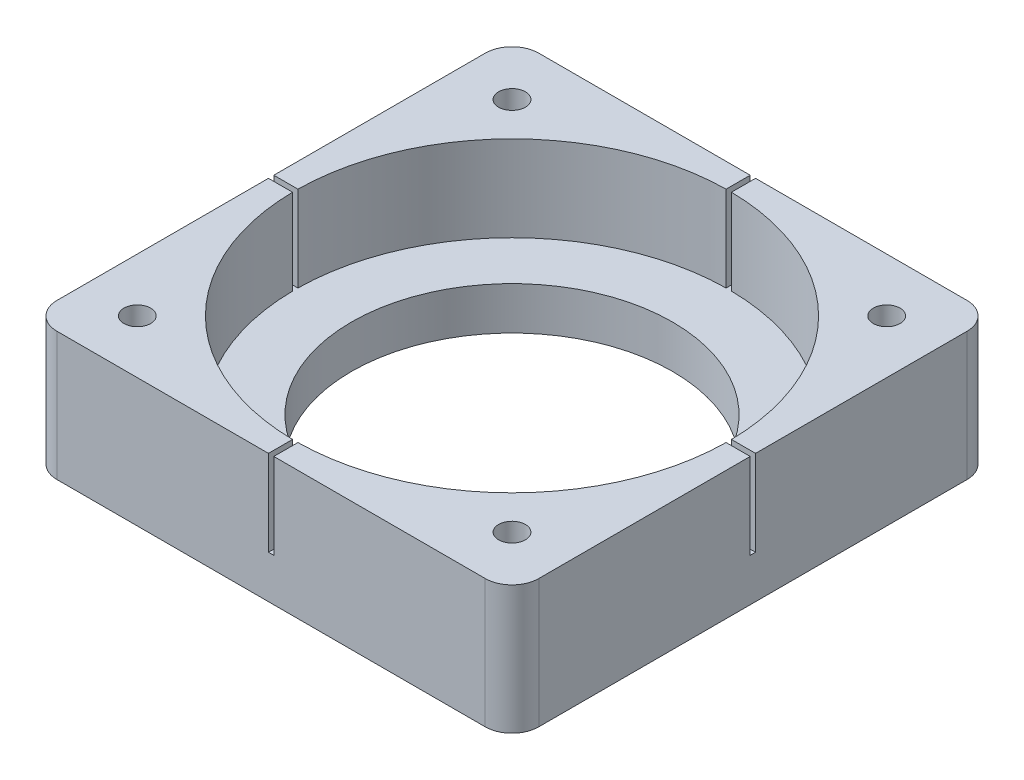
SolidWorks part; units mm, degrees
ref_plane "Front Plane" through (0, 0, 0) normal (0, 0, 1) x (1, 0, 0)
ref_plane "Top Plane" through (0, 0, 0) normal (0, 1, 0) x (1, 0, 0)
ref_plane "Right Plane" through (0, 0, 0) normal (1, 0, 0) x (0, 0, -1)
sketch "Sketch1" plane through (0, 0, 0) normal (0, 1, 0) x (1, 0, 0)
  line L5 (-45, -45) -> (45, -45)
  line L6 (-45, -45) -> (-45, 45)
  line L11 (-45, 45) -> (45, 45)
  line L12 (45, -45) -> (45, 45)
  line L13 (-45, -45) -> (45, 45) construction
  line L14 (-45, 45) -> (45, -45) construction
  line L15 (-35, -35) -> (35, -35) construction
  line L16 (-35, -35) -> (-35, 35) construction
  line L17 (-35, 35) -> (35, 35) construction
  line L18 (35, -35) -> (35, 35) construction
  line L19 (-35, -35) -> (35, 35) construction
  line L20 (-35, 35) -> (35, -35) construction
  circle A0 centre (0, 0) radius 34
  point P0 (0, 0)
  point P6 (0, 0)
  dimension "D3" = 68
  dimension "D1" = 70
  dimension "D2" = 90
extrude "Boss-Extrude1" add sketch "Sketch1" along normal blind 24 contours A0 | L5 L12 L11 L6 A0
sketch "Sketch2" plane through (0, 24, 0) normal (0, 1, 0) x (1, 0, 0)
  circle A0 centre (0, 0) radius 40.5
  dimension "D1" = 81
extrude "Cut-Extrude1" cut sketch "Sketch2" against normal blind 16
sketch "Sketch3" plane through (0, 8, 0) normal (0, 1, 0) x (1, 0, 0)
  circle A0 centre (0, 0) radius 12.7
  dimension "D1" = 25.4
extrude "Cut-Extrude2" cut sketch "Sketch3" against normal blind 19
hole_wizard "M6x1.0 Tapped Hole1" positions "Sketch4" profile "Sketch6" tap size "M6x1.0" standard "ANSI Metric" end condition through all
sketch "Sketch4" plane through (0, 0, 0) normal (0, -1, 0) x (-1, 0, 0)
  point P0 (35, 35)
  point P3 (35, -35)
  point P6 (-35, -35)
  point P9 (-35, 35)
cosmetic thread "Hole Thread1" parameters "D2"=6
cosmetic thread "Hole Thread2" parameters "D2"=6
cosmetic thread "Hole Thread3" parameters "D2"=6
cosmetic thread "Hole Thread4" parameters "D2"=6
sketch "Sketch6" plane through (-35, 0, -35) normal (1, 0, 0) x (0, 0, -1)
  line L0 (0, 0) -> (0, 24)
  line L1 (0, 24) -> (2.5, 24)
  line L2 (2.5, 24) -> (2.5, 0)
  line L5 (2.5, 0) -> (0, 0)
  line L11 (0, -6.35) -> (0, 107.95) construction
  dimension "Thru Tap Drill Dia." = 5
  dimension "Thru Tap Drill Depth" = 24
fillet "Fillet1" radius 5 4 edges at (45, 12, -45) (-45, 12, -45) (45, 12, 45) (-45, 12, 45)
chamfer "Chamfer1" [suppressed] distance 1 angle 45
sketch "Sketch7" plane through (0, 8, 0) normal (0, 1, 0) x (1, 0, 0)
  circle A0 centre (0, 0) radius 30
  circle A1 centre (0, 0) radius 20
  circle M1 centre (0, 0) radius 12.7
  dimension "D1" = 60
  dimension "D2" = 40
extrude "Cut-Extrude3" cut sketch "Sketch7" against normal through all contours A0 A1 | A1 M1
sketch "Sketch8" plane through (0, 24, 0) normal (0, 1, 0) x (1, 0, 0)
  line L0 (49.3592, 0.5) -> (35.5338, 0.5)
  line L1 (-0.5, 49.3592) -> (0.5, 49.3592)
  line L2 (-0.5, 49.3592) -> (-0.5, 35.5338)
  line L3 (-0.5, 35.5338) -> (0.5, 35.5338)
  line L4 (0.5, 49.3592) -> (0.5, 35.5338)
  line L5 (-0.5, 49.3592) -> (0.5, 35.5338) construction
  line L6 (-0.5, 35.5338) -> (0.5, 49.3592) construction
  line L7 (49.3592, 0.5) -> (49.3592, -0.5)
  line L8 (49.3592, -0.5) -> (35.5338, -0.5)
  line L9 (35.5338, 0.5) -> (35.5338, -0.5)
  line L10 (0.5, -49.3592) -> (0.5, -35.5338)
  line L11 (0.5, -49.3592) -> (-0.5, -49.3592)
  line L12 (-0.5, -49.3592) -> (-0.5, -35.5338)
  line L13 (0.5, -35.5338) -> (-0.5, -35.5338)
  line L14 (-49.3592, -0.5) -> (-35.5338, -0.5)
  line L15 (-49.3592, -0.5) -> (-49.3592, 0.5)
  line L16 (-49.3592, 0.5) -> (-35.5338, 0.5)
  line L17 (-35.5338, -0.5) -> (-35.5338, 0.5)
  point P0 (0, 42.4465)
  point P21 (0, 0)
  dimension "D1" = 1
  dimension "D2" = 4
extrude "Cut-Extrude4" cut sketch "Sketch8" against normal up to surface (16 mm away) up to face at (0, 8, 30)
